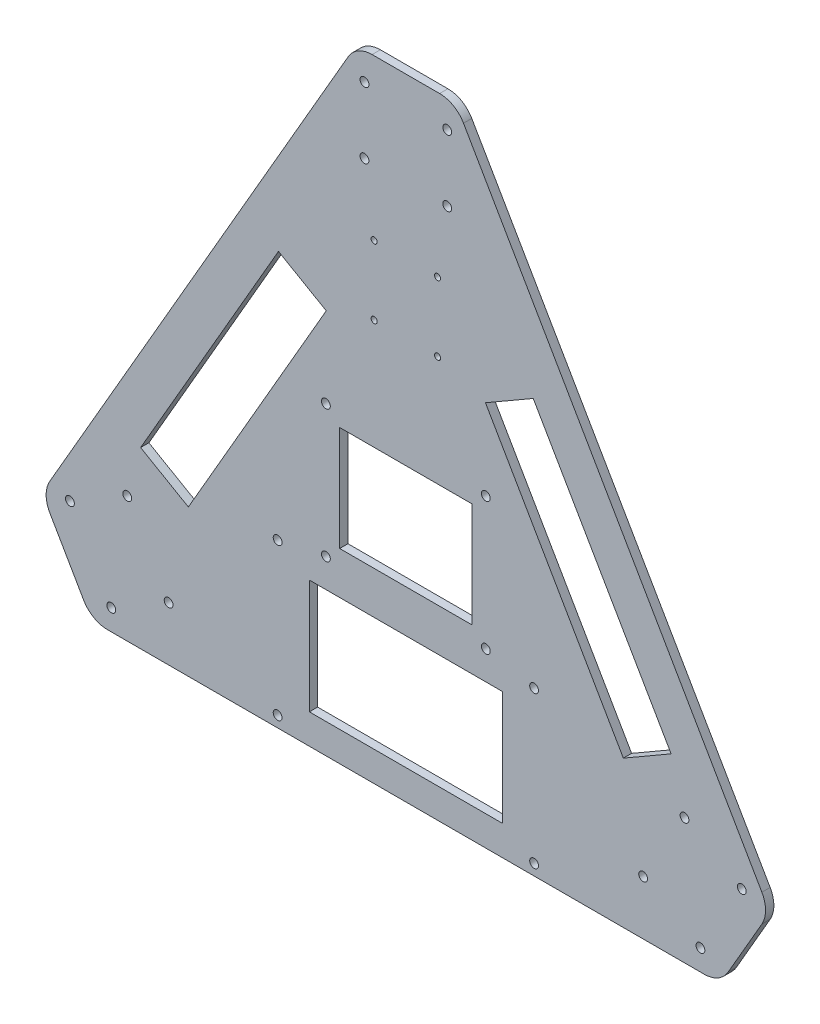
SolidWorks part; units mm, degrees
ref_plane "前视基准面" through (0, 0, 0) normal (0, 0, 1) x (1, 0, 0)
ref_plane "上视基准面" through (0, 0, 0) normal (0, 1, 0) x (1, 0, 0)
ref_plane "右视基准面" through (0, 0, 0) normal (1, 0, 0) x (0, 0, -1)
sketch "草图1" plane through (0, 0, 0) normal (0, 0, 1) x (1, 0, 0)
  line L0 (-18.0163, 142) -> (-131.9837, -55.3975)
  line L1 (-113.9675, -86.6025) -> (113.9675, -86.6025)
  line L2 (131.9837, -55.3975) -> (18.0163, 142)
  line L3 (0, 0) -> (150, -86.6025) construction
  line L4 (-15, 132) -> (15, 132) construction
  line L5 (-15, 132) -> (-15, 108) construction
  line L6 (-15, 108) -> (15, 108) construction
  line L7 (15, 132) -> (15, 108) construction
  line L8 (-15, 132) -> (15, 108) construction
  line L9 (-15, 108) -> (15, 132) construction
  line L10 (0, 0) -> (-150, -86.6025) construction
  line L11 (-121.8154, -53.0096) -> (-106.8154, -78.9904) construction
  line L12 (-121.8154, -53.0096) -> (-101.0307, -41.0096) construction
  line L13 (-106.8154, -78.9904) -> (-86.0307, -66.9904) construction
  line L14 (-101.0307, -41.0096) -> (-86.0307, -66.9904) construction
  line L15 (101.0307, -41.0096) -> (86.0307, -66.9904) construction
  line L16 (101.0307, -41.0096) -> (121.8154, -53.0096) construction
  line L17 (86.0307, -66.9904) -> (106.8154, -78.9904) construction
  line L18 (121.8154, -53.0096) -> (106.8154, -78.9904) construction
  line L19 (-11.5, 84) -> (11.5, 84) construction
  line L20 (-29, -24) -> (29, -24) construction
  line L21 (-29, -24) -> (-29, 24) construction
  line L22 (-29, 24) -> (29, 24) construction
  line L23 (29, -24) -> (29, 24) construction
  line L24 (-29, -24) -> (29, 24) construction
  line L25 (-29, 24) -> (29, -24) construction
  line L26 (-24, -19) -> (24, -19)
  line L27 (-24, -19) -> (-24, 19)
  line L28 (-24, 19) -> (24, 19)
  line L29 (24, -19) -> (24, 19)
  line L30 (-24, -19) -> (24, 19) construction
  line L31 (-24, 19) -> (24, -19) construction
  line L32 (-11.5, 84) -> (-11.5, 59) construction
  line L33 (11.5, 84) -> (11.5, 59) construction
  line L34 (-11.5, 59) -> (11.5, 59) construction
  line L35 (-46.188, 63.2051) -> (-28.8675, 53.2051)
  line L36 (-46.5, -82.6025) -> (46.5, -82.6025) construction
  line L37 (-46.5, -82.6025) -> (-46.5, -27.6025) construction
  line L38 (-46.5, -27.6025) -> (46.5, -27.6025) construction
  line L39 (46.5, -82.6025) -> (46.5, -27.6025) construction
  line L40 (-46.5, -82.6025) -> (46.5, -27.6025) construction
  line L41 (-46.5, -27.6025) -> (46.5, -82.6025) construction
  line L42 (-46.188, 63.2051) -> (-96.188, -23.3975)
  line L43 (-28.8675, 53.2051) -> (-78.8675, -33.3975)
  line L44 (-96.188, -23.3975) -> (-78.8675, -33.3975)
  line L45 (-35, -34.4036) -> (-35, -75.8015)
  line L46 (-35, -34.4036) -> (35, -34.4036)
  line L47 (-35, -75.8015) -> (35, -75.8015)
  line L48 (35, -34.4036) -> (35, -75.8015)
  line L49 (46.188, 63.2051) -> (28.8675, 53.2051)
  line L50 (46.188, 63.2051) -> (96.188, -23.3975)
  line L51 (28.8675, 53.2051) -> (78.8675, -33.3975)
  line L52 (96.188, -23.3975) -> (78.8675, -33.3975)
  line L53 (-131.9837, -55.3975) -> (-113.9675, -86.6025)
  line L54 (-18.0163, 142) -> (18.0163, 142)
  line L55 (131.9837, -55.3975) -> (113.9675, -86.6025)
  line L56 (-131.9837, -55.3975) -> (-150, -86.6025) construction
  line L57 (-150, -86.6025) -> (-113.9675, -86.6025) construction
  line L58 (131.9837, -55.3975) -> (150, -86.6025) construction
  line L59 (150, -86.6025) -> (113.9675, -86.6025) construction
  line L60 (-18.0163, 142) -> (0, 173.2051) construction
  line L61 (0, 173.2051) -> (18.0163, 142) construction
  circle A0 centre (0, 0) radius 120 construction
  circle A1 centre (-15, 132) radius 1.6
  circle A2 centre (15, 132) radius 1.6
  circle A3 centre (15, 108) radius 1.6
  circle A4 centre (-15, 108) radius 1.6
  circle A5 centre (-29, 24) radius 1.6
  circle A6 centre (-29, -24) radius 1.6
  circle A7 centre (-86.0307, -66.9904) radius 1.6
  circle A8 centre (29, -24) radius 1.6
  circle A9 centre (29, 24) radius 1.6
  circle A10 centre (101.0307, -41.0096) radius 1.6
  circle A11 centre (86.0307, -66.9904) radius 1.6
  circle A12 centre (106.8154, -78.9904) radius 1.6
  circle A13 centre (121.8154, -53.0096) radius 1.6
  circle A14 centre (-101.0307, -41.0096) radius 1.6
  circle A15 centre (-121.8154, -53.0096) radius 1.6
  circle A16 centre (-106.8154, -78.9904) radius 1.6
  circle A17 centre (-11.5, 84) radius 1.1
  circle A18 centre (11.5, 84) radius 1.1
  circle A19 centre (11.5, 59) radius 1.1
  circle A20 centre (-11.5, 59) radius 1.1
  circle A21 centre (-46.5, -27.6025) radius 1.6
  circle A22 centre (-46.5, -82.6025) radius 1.6
  circle A23 centre (46.5, -82.6025) radius 1.6
  circle A24 centre (46.5, -27.6025) radius 1.6
  point P0 (0, 0)
  point P3 (0, 120)
  point P51 (0, -55.1025)
  dimension "D14" = 240
  dimension "D18" = 3.2
  dimension "D25" = 2.2
  dimension "D30" = 3.2
  dimension "D1" = 60
  dimension "D3" = 24
  dimension "D4" = 30
  dimension "D5" = 30
  dimension "D6" = 24
  dimension "D7" = 30
  dimension "D8" = 24
  dimension "D9" = 15
  dimension "D10" = 15
  dimension "D11" = 58
  dimension "D12" = 48
  dimension "D13" = 300
  dimension "D15" = 108
  dimension "D16" = 108
  dimension "D17" = 10
  dimension "D19" = 25
  dimension "D20" = 23
  dimension "D21" = 60
  dimension "D22" = 11.5
  dimension "D23" = 5
  dimension "D24" = 5
  dimension "D26" = 93
  dimension "D27" = 55
  dimension "D28" = 4
  dimension "D29" = 46.5
  dimension "D31" = 15
  dimension "D32" = 15
  dimension "D33" = 20
  dimension "D34" = 20
  dimension "D35" = 70
  dimension "D36" = 100
  dimension "D37" = 110
  dimension "D39" = 60
  dimension "D40" = 120
  dimension "D41" = 60
  dimension "D42" = 10
  dimension "D43" = 10
extrude "凸台-拉伸1" add sketch "草图1" along normal blind 3
fillet "圆角1" radius 10 6 edges at (18.0163, 142, 1.5) (-18.0163, 142, 1.5) (131.9837, -55.3975, 1.5) (113.9675, -86.6025, 1.5) (-113.9675, -86.6025, 1.5) (-131.9837, -55.3975, 1.5)
